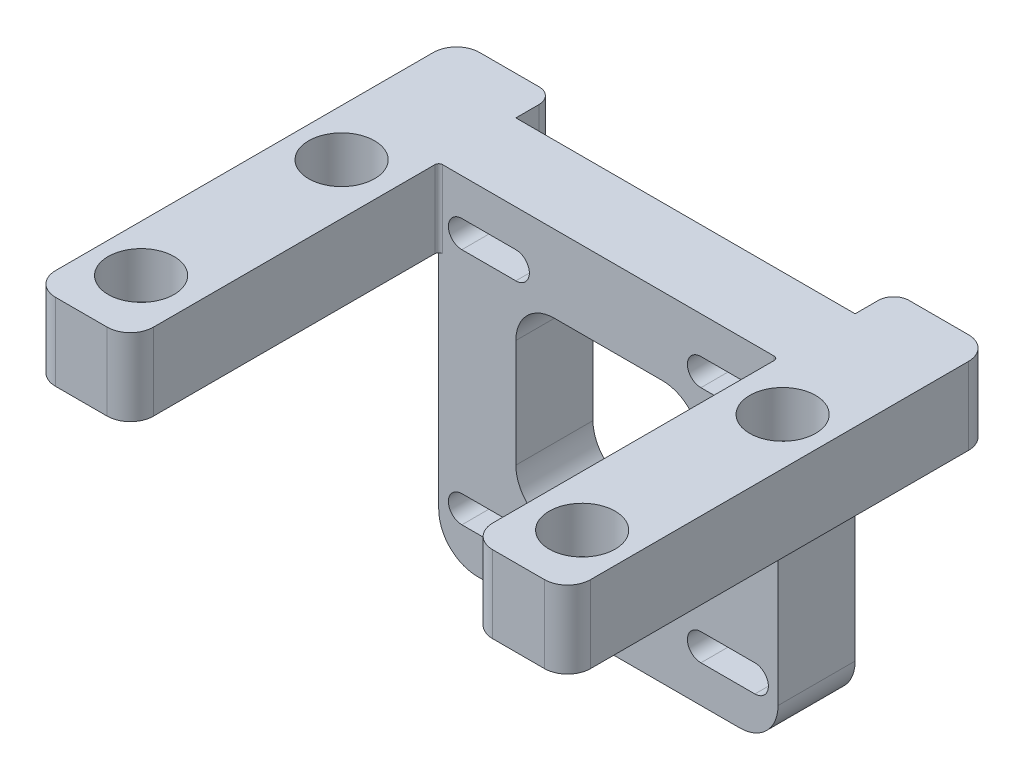
SolidWorks part; units mm, degrees
ref_plane "Front Plane" through (0, 0, 0) normal (0, 0, 1) x (1, 0, 0)
ref_plane "Top Plane" through (0, 0, 0) normal (0, 1, 0) x (1, 0, 0)
ref_plane "Right Plane" through (0, 0, 0) normal (1, 0, 0) x (0, 0, -1)
sketch "Sketch1" plane through (0, 0, 0) normal (0, 0, 1) x (1, 0, 0)
  line L0 (-19, 15.45) -> (-10.25, 15.45) construction
  line L1 (-22, 22) -> (22, 22)
  line L2 (-22, 22) -> (-22, -22)
  line L3 (-22, -22) -> (22, -22)
  line L4 (22, 22) -> (22, -22)
  line L5 (-22, 22) -> (22, -22) construction
  line L6 (-22, -22) -> (22, 22) construction
  line L7 (7, 12) -> (-7, 12)
  line L8 (12, 7) -> (12, -7)
  line L9 (7, -12) -> (-7, -12)
  line L10 (-12, 7) -> (-12, -7)
  line L11 (12, 12) -> (-12, -12) construction
  line L12 (12, -12) -> (-12, 12) construction
  line L13 (-19, 17.2) -> (-12, 17.2)
  line L14 (-19, 13.7) -> (-12, 13.7)
  line L15 (0, 0) -> (50000, 0) construction
  line L16 (-19, -17.2) -> (-12, -17.2)
  line L19 (12, 17.2) -> (19, 17.2)
  line L20 (12, 13.7) -> (19, 13.7)
  line L21 (10.25, 15.45) -> (19, 15.45) construction
  line L22 (-19, -13.7) -> (-12, -13.7)
  line L23 (12, -13.7) -> (19, -13.7)
  line L24 (12, -17.2) -> (19, -17.2)
  arc A0 (-12, -7) -> (-7, -12) centre (-7, -7) ccw
  arc A1 (7, -12) -> (12, -7) centre (7, -7) ccw
  arc A2 (12, 7) -> (7, 12) centre (7, 7) ccw
  arc A3 (-7, 12) -> (-12, 7) centre (-7, 7) ccw
  arc A4 (-19, 17.2) -> (-19, 13.7) centre (-19, 15.45) ccw
  arc A5 (19, 13.7) -> (19, 17.2) centre (19, 15.45) ccw
  circle A8 centre (0, 0) radius 12 construction
  arc A9 (12, 17.2) -> (12, 13.7) centre (12, 15.45) ccw
  arc A10 (-12, 17.2) -> (-12, 13.7) centre (-12, 15.45) cw
  arc A11 (-19, -17.2) -> (-19, -13.7) centre (-19, -15.45) cw
  arc A12 (-12, -17.2) -> (-12, -13.7) centre (-12, -15.45) ccw
  arc A13 (12, -17.2) -> (12, -13.7) centre (12, -15.45) cw
  arc A14 (19, -13.7) -> (19, -17.2) centre (19, -15.45) cw
  point P0 (0, 0)
  point P6 (0, 0)
  dimension "D4" = 5
  dimension "D9" = 1.75
  dimension "D1" = 44
  dimension "D2" = 44
  dimension "D3" = 24
  dimension "D5" = 38
  dimension "D6" = 1.75
  dimension "D7" = 15.45
  dimension "D8" = 7
extrude "Boss-Extrude1" add sketch "Sketch1" along normal blind 10
sketch "Sketch2" plane through (22, 0, 0) normal (1, 0, 0) x (0, 0, -1)
  line L0 (5, 12) -> (-50, 12)
  line L2 (5, 12) -> (5, 22)
  line L4 (-50, 12) -> (-50, 16)
  line L5 (-50, 16) -> (-15.3222, 16) construction
  line L6 (5, 22) -> (-50, 22)
  line L7 (-50, 22) -> (-50, 16)
  line L8 (-10, 22) -> (0, 22) construction
  line L12 (0, -22) -> (0, 22) construction
  dimension "D4" = 5
  dimension "D1" = 4
  dimension "D2" = 55
  dimension "D3" = 12
extrude "Boss-Extrude2" add sketch "Sketch2" along normal blind 12.7
sketch "Sketch3" plane through (0, 12, 0) normal (0, -1, 0) x (1, 0, 0)
  line L1 (34.7, 50) -> (34.7, -5) construction
  circle A0 centre (28.6, 42) radius 2.6
  circle A1 centre (28.6, 16) radius 2.6
  dimension "D2" = 5.2
  dimension "D1" = 6.1
  dimension "D3" = 8
  dimension "D4" = 26
extrude "Cut-Extrude1" cut sketch "Sketch3" against normal through all
ref_plane "Plane1" through (0, 16, 0) normal (0, -1, 0) x (-1, 0, 0)
sketch "Sketch4" plane through (0, 16, 0) normal (0, -1, 0) x (-1, 0, 0)
  circle A0 centre (-28.6, -16) radius 4.275
  circle A1 centre (-28.6, -42) radius 4.275
  dimension "D1" = 8.55
  dimension "D2" = 8.55
extrude "Cut-Extrude2" cut sketch "Sketch4" against normal through all
ref_plane "Plane2" through (0, 0, 0) normal (1, 0, 0) x (0, 0, -1)
mirror "Mirror1" about plane through (0, 0, 0) normal (1, 0, 0) of "Cut-Extrude1", "Boss-Extrude2", "Cut-Extrude2"
fillet "Fillet1" radius 3 6 edges at (34.7, 17, -5) (34.7, 17, 50) (-34.7, 17, -5) (-34.7, 17, 50) (-22, 17, 50) (22, 17, 50)
fillet "Fillet2" radius 5 2 edges at (22, -22, 5) (-22, -22, 5)
fillet "Fillet3" radius 0.5 2 edges at (-22, 17, 10) (22, 17, 10)
fillet "Fillet4" radius 2 2 edges at (22, 17, -5) (-22, 17, -5)
